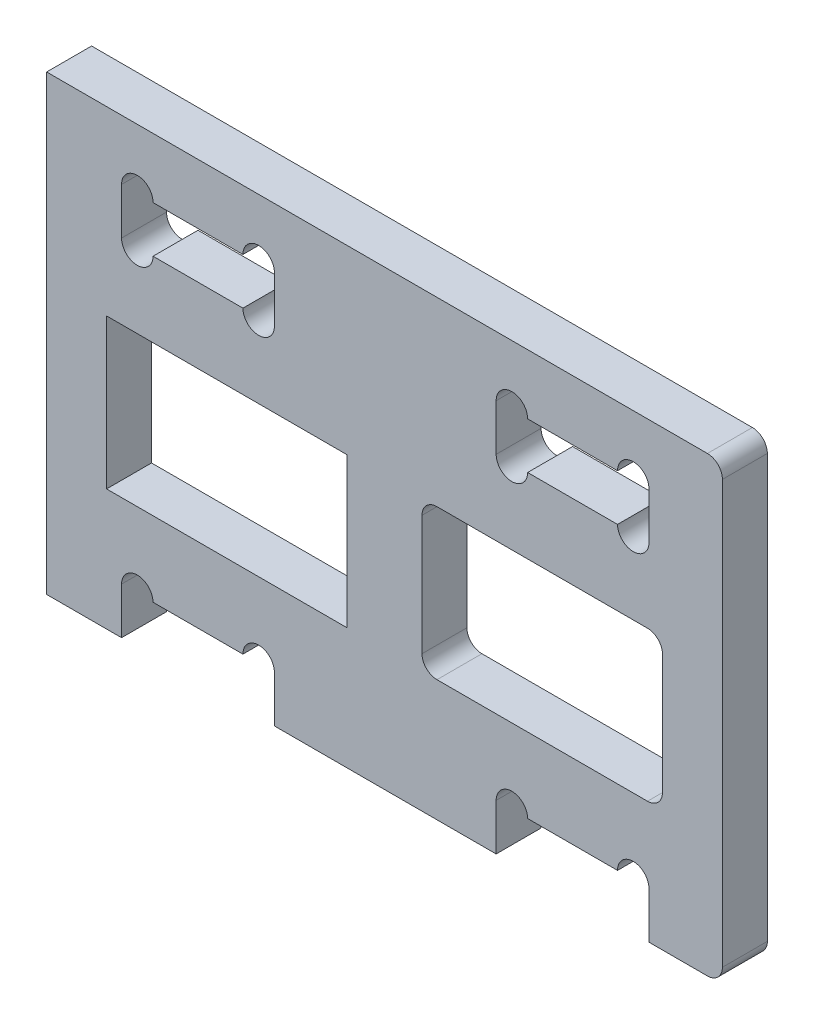
SolidWorks part; units mm, degrees
ref_plane "前视基准面" through (0, 0, 0) normal (0, 0, 1) x (1, 0, 0)
ref_plane "上视基准面" through (0, 0, 0) normal (0, 1, 0) x (1, 0, 0)
ref_plane "右视基准面" through (0, 0, 0) normal (1, 0, 0) x (0, 0, -1)
sketch "草图1" plane through (0, 0, 0) normal (0, 0, 1) x (1, 0, 0)
  line L0 (-5.1, -15.1) -> (-10, -15.1)
  line L1 (10, -15.1) -> (5.1, -15.1)
  line L2 (10, -15.1) -> (10, 15.1)
  line L3 (10, 15.1) -> (-10, 15.1)
  line L4 (-10, -15.1) -> (-10, 15.1) construction
  line L5 (10, -15.1) -> (-10, 15.1) construction
  line L6 (10, 15.1) -> (-10, -15.1) construction
  line L7 (5.1, -15.1) -> (-5.1, -15.1) construction
  line L8 (5.1, -15.1) -> (5.1, -12)
  line L9 (5.1, -12) -> (-5.1, -12)
  line L10 (-5.1, -15.1) -> (-5.1, -12)
  line L11 (5.1, -15.1) -> (-5.1, -12) construction
  line L12 (5.1, -12) -> (-5.1, -15.1) construction
  line L13 (5.1, 8) -> (-5.1, 8)
  line L14 (5.1, 8) -> (5.1, 11.1)
  line L15 (5.1, 11.1) -> (-5.1, 11.1)
  line L16 (-5.1, 8) -> (-5.1, 11.1)
  line L17 (5.1, 8) -> (-5.1, 11.1) construction
  line L18 (5.1, 11.1) -> (-5.1, 8) construction
  line L19 (-19.9, -15.1) -> (-19.9, -12)
  line L20 (6, -7) -> (-10.05, -7)
  line L21 (6, -7) -> (6, 3)
  line L22 (6, 3) -> (-10.05, 3)
  line L23 (-10.05, -7) -> (-10.05, 3)
  line L24 (6, -7) -> (-10.05, 3) construction
  line L25 (6, 3) -> (-10.05, -7) construction
  line L26 (-30.1, 8) -> (-19.9, 8)
  line L27 (-30.1, 8) -> (-30.1, 11.1)
  line L28 (-30.1, 11.1) -> (-19.9, 11.1)
  line L29 (-19.9, 8) -> (-19.9, 11.1)
  line L30 (-30.1, 8) -> (-19.9, 11.1) construction
  line L31 (-30.1, 11.1) -> (-19.9, 8) construction
  line L32 (-19.9, -12) -> (-30.1, -12)
  line L33 (-30.1, -12) -> (-30.1, -15.1)
  line L34 (-10, -15.1) -> (-19.9, -15.1)
  line L35 (-25, -12) -> (-25, -7.8555) construction
  line L36 (-10, 15.1) -> (-35.1, 15.1)
  line L37 (-35.1, 15.1) -> (-35.1, -15.1)
  line L38 (-35.1, -15.1) -> (-30.1, -15.1)
  line L40 (-31.1, -7) -> (-15.05, -7)
  line L41 (-31.1, -7) -> (-31.1, 3)
  line L42 (-31.1, 3) -> (-15.05, 3)
  line L43 (-15.05, -7) -> (-15.05, 3)
  line L44 (-31.1, -7) -> (-15.05, 3) construction
  line L45 (-31.1, 3) -> (-15.05, -7) construction
  circle A0 centre (-4.05, 11.1) radius 1.05
  circle A1 centre (4.05, 11.1) radius 1.05
  circle A2 centre (-4.05, 8) radius 1.05
  circle A3 centre (4.05, 8) radius 1.05
  circle A4 centre (-4.05, -12) radius 1.05
  circle A5 centre (4.05, -12) radius 1.05
  circle A6 centre (-20.95, -12) radius 1.05
  circle A7 centre (-29.05, -12) radius 1.05
  circle A8 centre (-20.95, 8) radius 1.05
  circle A9 centre (-29.05, 8) radius 1.05
  circle A10 centre (-29.05, 11.1) radius 1.05
  circle A11 centre (-20.95, 11.1) radius 1.05
  point P0 (0, 0)
  point P6 (0, -13.55)
  point P11 (0, 9.55)
  point P28 (-2.025, -2)
  point P33 (-25, 9.55)
  point P58 (-23.075, -2)
  dimension "D5" = 2.1
  dimension "D1" = 23.1
  dimension "D2" = 3.1
  dimension "D3" = 10.2
  dimension "D4" = 4
  dimension "D6" = 20
  dimension "D7" = 5
  dimension "D8" = 5
  dimension "D9" = 4
  dimension "D10" = 25
  dimension "D11" = 5
  dimension "D12" = 4
  dimension "D13" = 5
extrude "凸台-拉伸1" add sketch "草图1" along normal blind 3 contours A5 L8 L1 L2 L3 L4 L0 L10 A4 L9 A3 L13 A2 L16 A0 L15 A1 L14 L20 L23 L22 L21
fillet "圆角1" radius 1 6 edges at (10, 15.1, 1.5) (10, -15.1, 1.5) (6, -7, 1.5) (6, 3, 1.5) (-10.05, -7, 1.5) (-10.05, 3, 1.5)
